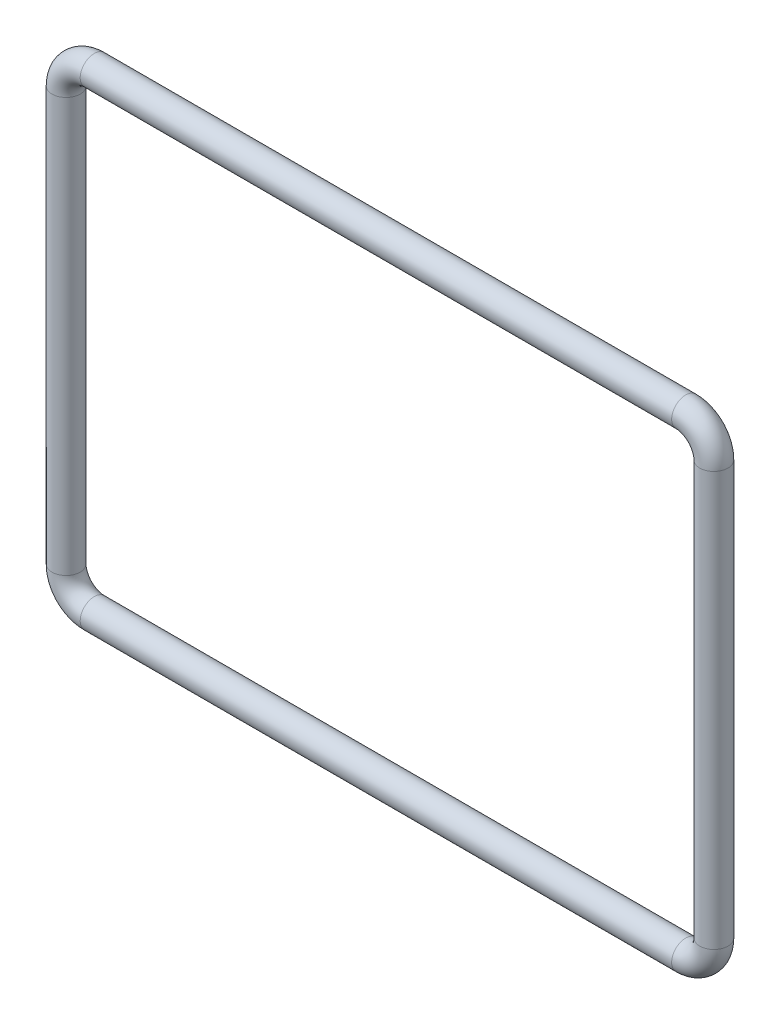
SolidWorks part; units mm, degrees
material "AISI 4130 Aço, normalizado a 870C"
ref_plane "Plano frontal" through (0, 0, 0) normal (0, 0, 1) x (1, 0, 0)
ref_plane "Plano superior" through (0, 0, 0) normal (0, 1, 0) x (1, 0, 0)
ref_plane "Plano direito" through (0, 0, 0) normal (1, 0, 0) x (0, 0, -1)
sketch "Esboço1" plane through (0, 0, 0) normal (0, 0, 1) x (1, 0, 0)
  line L0 (-100, 140) -> (-100, 0) construction
  line L1 (0, 0) -> (-200, 0) construction
  line L2 (0, 0) -> (0, 140) construction
  line L3 (0, 140) -> (-200, 140) construction
  line L4 (-200, 0) -> (-200, 140) construction
  line L5 (-200, 149.525) -> (0, 149.525)
  line L6 (-209.525, 140) -> (-209.525, 0)
  line L7 (-200, -9.525) -> (0, -9.525)
  line L8 (9.525, 0) -> (9.525, 140)
  line L9 (-200, 149.525) -> (-200, 144.7625) construction
  circle A0 centre (0, 0) radius 4.7625 construction
  circle A1 centre (-200, 0) radius 4.7625 construction
  circle A2 centre (-200, 140) radius 4.7625 construction
  circle A3 centre (0, 140) radius 4.7625 construction
  circle A4 centre (-200, 140) radius 9.525 construction
  circle A5 centre (0, 140) radius 9.525 construction
  circle A6 centre (-200, 0) radius 9.525 construction
  circle A7 centre (0, 0) radius 9.525 construction
  arc A8 (-200, 149.525) -> (-209.525, 140) centre (-200, 140) ccw
  arc A9 (-200, -9.525) -> (-209.525, 0) centre (-200, 0) cw
  arc A10 (9.525, 0) -> (0, -9.525) centre (0, 0) cw
  arc A11 (9.525, 140) -> (0, 149.525) centre (0, 140) ccw
  dimension "D1" = 9.525
  dimension "D2" = 140
  dimension "D3" = 200
  dimension "D4" = 4.7625
ref_plane "Plano1" through (-200, 0, 0) normal (1, 0, 0) x (0, 0, -1)
sketch "Esboço4" plane through (-200, 0, 0) normal (1, 0, 0) x (0, 0, -1)
  circle A0 centre (0, 149.525) radius 4.7625
sweep "Varredura1" add profiles "Esboço4" path "Esboço1"
ref_plane "Plano2" through (0, 0, 10) normal (0, 0, 1) x (1, 0, 0)
ref_plane "Plano3" through (-100, 0, 0) normal (1, 0, 0) x (0, 0, -1)
